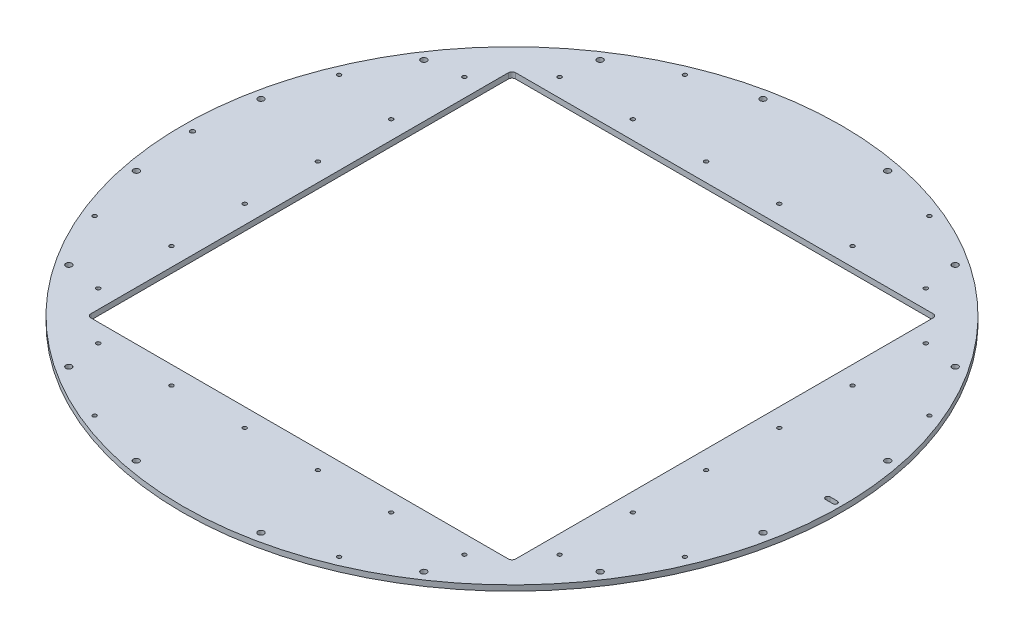
SolidWorks part; units mm, degrees
material "6061-T6 (SS)"
ref_plane "Front" through (0, 0, 0) normal (0, 0, 1) x (1, 0, 0)
ref_plane "Top" through (0, 0, 0) normal (0, 1, 0) x (1, 0, 0)
ref_plane "Right" through (0, 0, 0) normal (1, 0, 0) x (0, 0, -1)
sketch "Sketch1" plane through (0, 0, 0) normal (0, 1, 0) x (1, 0, 0)
  line L1 (-368.3, -368.3) -> (368.3, -368.3)
  line L2 (-368.3, -368.3) -> (-368.3, 368.3)
  line L3 (-368.3, 368.3) -> (368.3, 368.3)
  line L4 (368.3, -368.3) -> (368.3, 368.3)
  circle A0 centre (0, 0) radius 571.5
  dimension "D1" = 1143
  dimension "D2" = 736.6
  dimension "D3" = 736.6
  dimension "D4" = 368.3
  dimension "D5" = 368.3
extrude "Boss-Extrude1" add sketch "Sketch1" along normal blind 9.525
sketch "Sketch3" plane through (0, 9.525, 0) normal (0, 1, 0) x (1, 0, 0)
  line L0 (547.6875, 0) -> (560.3875, 0) construction
  line L3 (547.6875, 3.9688) -> (560.3875, 3.9688)
  line L4 (547.6875, -3.9688) -> (560.3875, -3.9687)
  line L5 (-554.0375, 0) -> (554.0375, 0) construction
  arc A4 (547.6875, 3.9688) -> (547.6875, -3.9688) centre (547.6875, 0) ccw
  arc A5 (560.3875, -3.9687) -> (560.3875, 3.9688) centre (560.3875, 0) ccw
  circle A6 centre (-554.0375, 0) radius 3.9687
  point P2 (554.0375, 0)
  point P15 (0, 0)
  dimension "D1" = 7.9375
  dimension "D2" = 7.9375
  dimension "D3" = 6.35
  dimension "D4" = 554.0375
extrude "Cut-Extrude1" cut sketch "Sketch3" against normal through all
hole_wizard "3/8 Clearance Hole1" positions "Sketch19" profile "Sketch20" hole size "3/8" standard "ANSI Inch" end condition through all
sketch "Sketch19" plane through (0, 0, 0) normal (0, -1, 0) x (-1, 0, 0)
  line L0 (0, 0) -> (-543.3918, -108.0874) construction
  line L3 (0, 0) -> (-554.0375, 0) construction
  point P0 (-543.3918, -108.0874)
  dimension "D1" = 11.25
  dimension "D2" = 554.0375
sketch "Sketch20" plane through (543.3918, 0, 108.0874) normal (1, 0, 0) x (0, 0, -1)
  line L0 (0, 0) -> (0, 9.525)
  line L1 (0, 9.525) -> (5.1587, 9.525)
  line L2 (5.1587, 9.525) -> (5.1587, 0)
  line L5 (5.1587, 0) -> (0, 0)
  line L11 (0, -6.35) -> (0, 107.95) construction
  dimension "Thru Hole Dia." = 10.3175
  dimension "Thru Hole Depth" = 9.525
pattern_circular "CirPattern - 16X 3/8 Clearance Holes" count 16 over 360 about axis through (0, 0, 0) along (0, 1, 0) of "3/8 Clearance Hole1"
hole_wizard "1/4 Box Holes 2" positions "Sketch7" profile "Sketch8" hole size "1/4" standard "ANSI Inch" end condition through all
sketch "Sketch7" plane through (0, 9.525, 0) normal (0, 1, 0) x (1, 0, 0)
  line L0 (-368.3, -368.3) -> (368.3, -368.3) construction
  line L1 (-368.3, 368.3) -> (-368.3, -368.3) construction
  point P0 (-317.5, -400.05)
  point P5 (0, -368.3)
  point P8 (-368.3, 0)
  dimension "D1" = 317.5
  dimension "D2" = 400.05
sketch "Sketch8" plane through (-317.5, 9.525, 400.05) normal (1, 0, 0) x (0, 0, 1)
  line L0 (0, 0) -> (0, 9.525)
  line L1 (0, 9.525) -> (3.3782, 9.525)
  line L2 (3.3782, 9.525) -> (3.3782, 0)
  line L5 (3.3782, 0) -> (0, 0)
  line L11 (0, -6.35) -> (0, 107.95) construction
  dimension "Thru Hole Dia." = 6.7564
  dimension "Thru Hole Depth" = 9.525
pattern_linear "LPattern1" count 6 spacing 127 along (1, 0, 0) count 2 spacing 800.1 along (0, 0, -1) of "1/4 Box Holes 2"
hole_wizard "1/4 Box Holes 1" positions "Sketch9" profile "Sketch10" hole size "1/4" standard "ANSI Inch" end condition through all
sketch "Sketch9" plane through (0, 9.525, 0) normal (0, 1, 0) x (1, 0, 0)
  line L0 (-368.3, 368.3) -> (-368.3, -368.3) construction
  line L1 (-368.3, -368.3) -> (368.3, -368.3) construction
  point P0 (-400.05, -317.5)
  point P5 (-368.3, 0)
  point P8 (0, -368.3)
  dimension "D1" = 317.5
  dimension "D2" = 400.05
sketch "Sketch10" plane through (-400.05, 9.525, 317.5) normal (1, 0, 0) x (0, 0, 1)
  line L0 (0, 0) -> (0, 9.525)
  line L1 (0, 9.525) -> (3.3782, 9.525)
  line L2 (3.3782, 9.525) -> (3.3782, 0)
  line L5 (3.3782, 0) -> (0, 0)
  line L11 (0, -6.35) -> (0, 107.95) construction
  dimension "Thru Hole Dia." = 6.7564
  dimension "Thru Hole Depth" = 9.525
pattern_linear "LPattern2" count 6 spacing 127 along (0, 0, -1) count 2 spacing 800.1 along (1, 0, 0) of "1/4 Box Holes 1"
hole_wizard "CSK for 1/4 Flat Head Machine Screw1" positions "Sketch17" profile "Sketch18" countersink size "1/4" standard "ANSI Inch" end condition through all
sketch "Sketch17" plane through (0, 0, 0) normal (0, -1, 0) x (-1, 0, 0)
  line L0 (0, 0) -> (-511.8639, 212.021) construction
  line L2 (0, 0) -> (-571.5, 0) construction
  circle A0 centre (0, 0) radius 571.5 construction
  point P0 (-511.8639, 212.021)
  dimension "D1" = 22.5
  dimension "D2" = 554.0375
sketch "Sketch18" plane through (511.8639, 0, -212.021) normal (1, 0, 0) x (0, 0, -1)
  line L0 (0, 0) -> (0, 9.525)
  line L1 (0, 9.525) -> (3.3782, 9.525)
  line L2 (3.3782, 9.525) -> (3.3782, 3.5209)
  line L3 (3.3782, 3.5209) -> (6.4389, 0)
  line L5 (6.4389, 0) -> (0, 0)
  line L6 (-3.3782, 3.5209) -> (-6.4389, 0) construction
  line L11 (0, -6.35) -> (0, 107.95) construction
  dimension "Thru Hole Dia." = 6.7564
  dimension "Thru Hole Depth" = 9.525
  dimension "Near C'Sink Dia." = 12.8778
  dimension "Near C'Sink Angle" = 82
pattern_circular "CirPattern4" count 8 over 360 about axis through (0, 0, 0) along (0, 1, 0) of "CSK for 1/4 Flat Head Machine Screw1"
fillet "Fillet1" radius 6.35 4 edges at (368.3, 4.7625, 368.3) (368.3, 4.7625, -368.3) (-368.3, 4.7625, -368.3) (-368.3, 4.7625, 368.3)
ref_plane "Sterling Mount Reference" through (0, 0, 0) normal (0, 1, 0) x (1, 0, 0)
